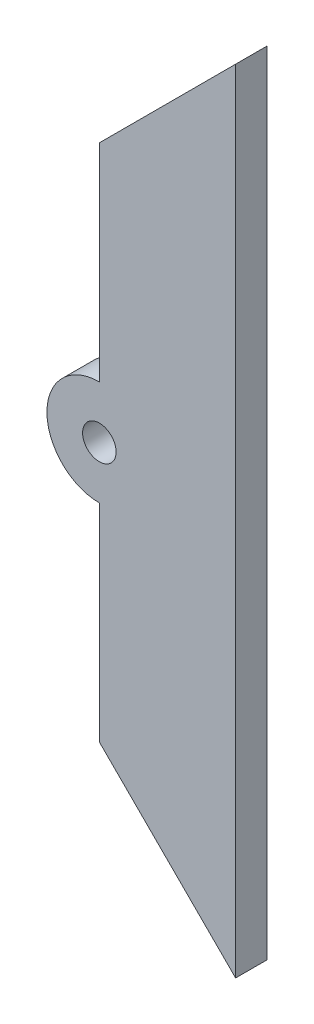
SolidWorks part; units mm, degrees
ref_plane "Front Plane" through (0, 0, 0) normal (0, 0, 1) x (1, 0, 0)
ref_plane "Top Plane" through (0, 0, 0) normal (0, 1, 0) x (1, 0, 0)
ref_plane "Right Plane" through (0, 0, 0) normal (1, 0, 0) x (0, 0, -1)
sketch "Sketch1" plane through (0, 0, 0) normal (0, 0, 1) x (1, 0, 0)
  line L0 (-13, -24.75) -> (-13, 24.75)
  line L5 (55, 0) -> (-55, 0) construction
  line L6 (-13, 24.75) -> (0, 37.75)
  line L7 (0, -55) -> (0, 55) construction
  line L8 (0, 37.75) -> (0, -37.75)
  line L9 (-13, -24.75) -> (0, -37.75)
  circle A4 centre (-13, 0) radius 5
  point P10 (0, 0)
  point P11 (-13, 0)
  dimension "D3" = 45
  dimension "D1" = 13
  dimension "D2" = 49.5
extrude "Boss-Extrude1" add sketch "Sketch1" along normal blind 3
sketch "Sketch2" plane through (0, 0, 3) normal (0, 0, 1) x (1, 0, 0)
  line L0 (1.65, 0) -> (-1.65, 0) construction
  circle A0 centre (-13, 0) radius 1.6
  arc A1 (-13, 5) -> (-13, -5) centre (-13, 0) ccw construction
  dimension "D1" = 3.2
extrude "Cut-Extrude1" cut sketch "Sketch2" against normal up to next
